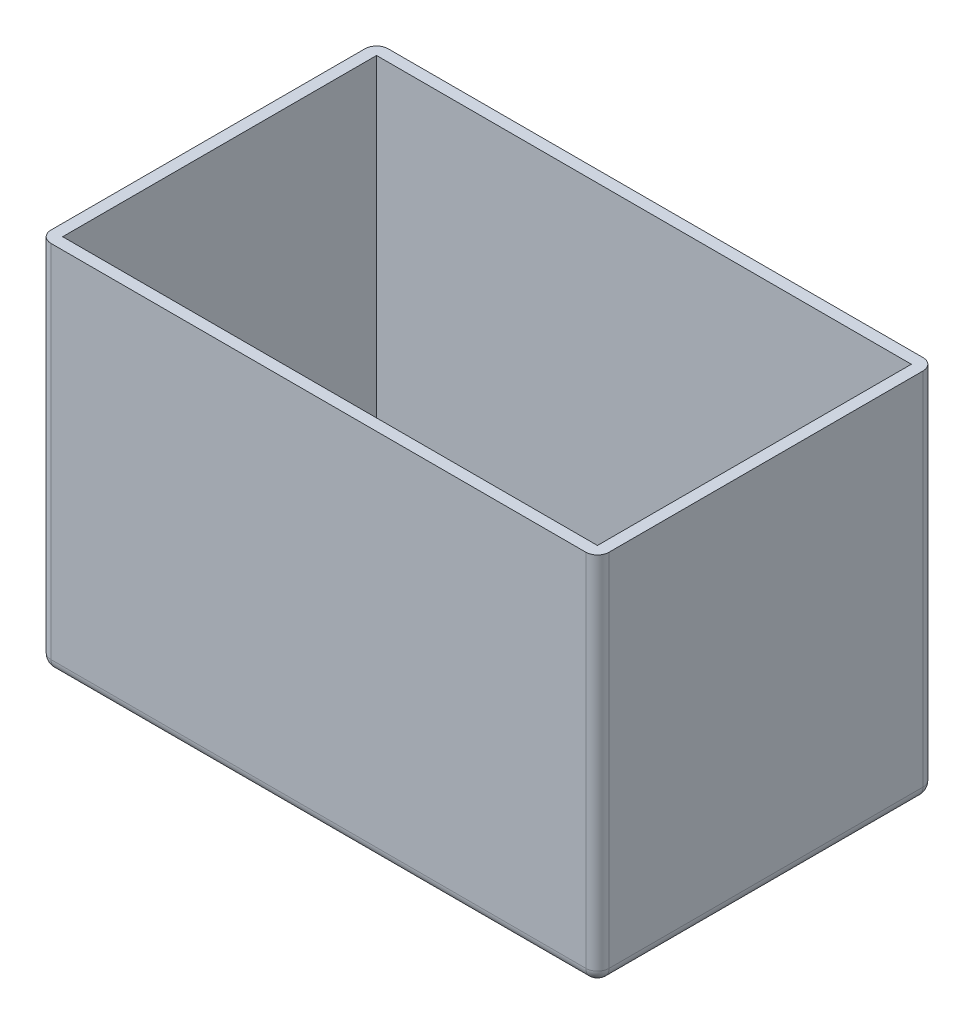
SolidWorks part; units mm, degrees
ref_plane "正面" through (0, 0, 0) normal (0, 0, 1) x (1, 0, 0)
ref_plane "平面" through (0, 0, 0) normal (0, 1, 0) x (1, 0, 0)
ref_plane "右側面" through (0, 0, 0) normal (1, 0, 0) x (0, 0, -1)
sketch "ｽｹｯﾁ1" plane through (0, 0, 0) normal (0, 1, 0) x (1, 0, 0)
  line L0 (-32.7097, 26.4477) -> (15.2903, 26.4477)
  line L1 (-32.7097, 26.4477) -> (-32.7097, 55.4477)
  line L2 (15.2903, 26.4477) -> (15.2903, 55.4477)
  line L3 (-32.7097, 55.4477) -> (15.2903, 55.4477)
  dimension "D1" = 29
  dimension "D2" = 48
extrude "ﾎﾞｽ - 押し出し1" add sketch "ｽｹｯﾁ1" along normal blind 32
sketch "ｽｹｯﾁ4" plane through (0, 32, 0) normal (0, 1, 0) x (1, 0, 0)
  line L0 (-31.7097, 54.4477) -> (-31.7097, 27.4477)
  line L1 (-31.7097, 54.4477) -> (14.2903, 54.4478)
  line L2 (-31.7097, 27.4477) -> (14.2903, 27.4477)
  line L3 (14.2903, 54.4478) -> (14.2903, 27.4477)
  line L6 (15.2903, 55.4477) -> (-32.7097, 55.4477) construction
  line L7 (15.2903, 26.4477) -> (15.2903, 55.4477) construction
  point P4 (-8.7097, 40.9477)
  point P8 (-8.7097, 40.9477)
  dimension "D1" = 46
  dimension "D2" = 27
  dimension "D3" = 23
  dimension "D4" = 13.5
  dimension "D5" = 14.5
  dimension "D6" = 24
extrude "ｶｯﾄ - 押し出し1" cut sketch "ｽｹｯﾁ4" against normal blind 31 contours L1 L3 L2 L0
fillet "ﾌｨﾚｯﾄ1" radius 1 8 edges at (-32.7097, 0, -40.9477) (-8.7097, 0, -55.4477) (15.2903, 0, -40.9477) (-8.7097, 0, -26.4477) (15.2903, 16, -26.4477) (15.2903, 16, -55.4477) (-32.7097, 16, -26.4477) (-32.7097, 16, -55.4477)
sketch "ｽｹｯﾁ5" plane through (0, 0, 0) normal (0, -1, 0) x (-1, 0, 0)
  line L0 (31.7097, 54.4477) -> (-14.2903, 54.4477) construction
  line L1 (-14.2903, 54.4477) -> (-14.2903, 27.4477) construction
  circle A0 centre (-3.2603, 44.3466) radius 8
  circle A1 centre (22.3397, 44.3467) radius 8
  point P4 (10.25, 54.4477)
  point P5 (-11.2603, 44.3466)
  point P8 (-14.2903, 44.3466)
  dimension "D1" = 25.6
  dimension "D2" = 16
  dimension "D3" = 16
  dimension "D4" = 3.03
extrude "ｶｯﾄ - 押し出し2" cut sketch "ｽｹｯﾁ5" against normal blind 1
